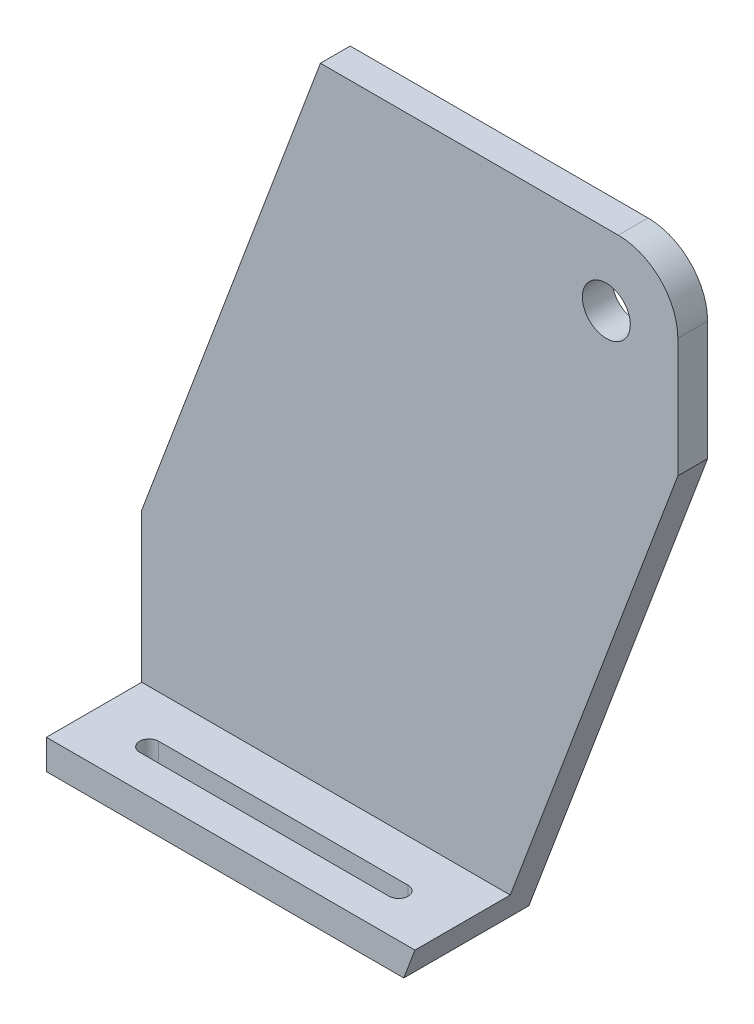
SolidWorks part; units mm, degrees
ref_plane "Front Plane" through (0, 0, 0) normal (0, 0, 1) x (1, 0, 0)
ref_plane "Top Plane" through (0, 0, 0) normal (0, 1, 0) x (1, 0, 0)
ref_plane "Right Plane" through (0, 0, 0) normal (1, 0, 0) x (0, 0, -1)
sketch "Sketch2" plane through (0, 0, 0) normal (0, 0, 1) x (1, 0, 0)
  line L1 (-45, 2.5) -> (45, 2.5)
  line L2 (-45, 2.5) -> (-45, -2.5)
  line L3 (-45, -2.5) -> (45, -2.5)
  line L4 (45, 2.5) -> (45, -2.5)
  line L5 (-45, 2.5) -> (45, -2.5) construction
  line L6 (-45, -2.5) -> (45, 2.5) construction
  point P0 (0, 0)
  dimension "D1" = 5
  dimension "D2" = 90
extrude "Boss-Extrude1" add sketch "Sketch2" along normal blind 21
sketch "Sketch3" plane through (0, 2.5, 0) normal (0, 1, 0) x (1, 0, 0)
  line L0 (45, -21) -> (45, 0) construction
  line L1 (-45, 0) -> (45, 0)
  line L2 (-45, 0) -> (-45, -5)
  line L3 (-45, -5) -> (45, -5)
  line L4 (45, 0) -> (45, -5)
  dimension "D1" = 5
extrude "Boss-Extrude2" add sketch "Sketch3" along normal blind 105
fillet "Fillet1" radius 10 1 edges at (45, 107.5, 2.5)
sketch "Sketch4" plane through (0, 0, 5) normal (0, 0, 1) x (1, 0, 0)
  line L0 (-45, 107.5) -> (35, 107.5) construction
  line L2 (45, 97.5) -> (45, 2.5) construction
  circle A0 centre (33, 95.5) radius 4.025
  dimension "D1" = 8.05
  dimension "D2" = 12
  dimension "D3" = 12
extrude "Cut-Extrude1" cut sketch "Sketch4" against normal through all
sketch "Sketch6" plane through (0, 0, 21) normal (0, 0, 1) x (1, 0, 0)
  line L0 (45, 77.5) -> (15, -2.5)
  line L1 (45, 97.5) -> (45, 2.5) construction
  line L2 (-45, -2.5) -> (45, -2.5) construction
  line L3 (15, -2.5) -> (45, -2.5)
  line L4 (45, -2.5) -> (45, 77.5)
  line L5 (-45, 27.5) -> (-15, 107.5)
  line L6 (-45, 107.5) -> (-45, 2.5) construction
  line L8 (-45, 27.5) -> (-45, 107.5)
  line L9 (-45, 107.5) -> (35, 107.5) construction
  line L10 (-45, 107.5) -> (-15, 107.5)
  dimension "D1" = 80
  dimension "D2" = 30
  dimension "D3" = 30
extrude "Cut-Extrude2" cut sketch "Sketch6" against normal through all
sketch "Sketch7" plane through (0, 2.5, 0) normal (0, 1, 0) x (1, 0, 0)
  line L0 (6.875, -13.75) -> (-35, -13.75) construction
  line L1 (6.875, -15.35) -> (-35, -15.35)
  line L2 (6.875, -12.15) -> (-35, -12.15)
  line L3 (16.875, -21) -> (-45, -21) construction
  line L4 (-45, -21) -> (-45, -5) construction
  line L5 (16.875, -21) -> (16.875, -5) construction
  arc A0 (6.875, -15.35) -> (6.875, -12.15) centre (6.875, -13.75) ccw
  arc A1 (-35, -12.15) -> (-35, -15.35) centre (-35, -13.75) ccw
  point P2 (-14.0625, -13.75)
  dimension "D1" = 1.6
  dimension "D2" = 7.25
  dimension "D3" = 10
  dimension "D4" = 10
extrude "Cut-Extrude3" cut sketch "Sketch7" against normal blind 10
